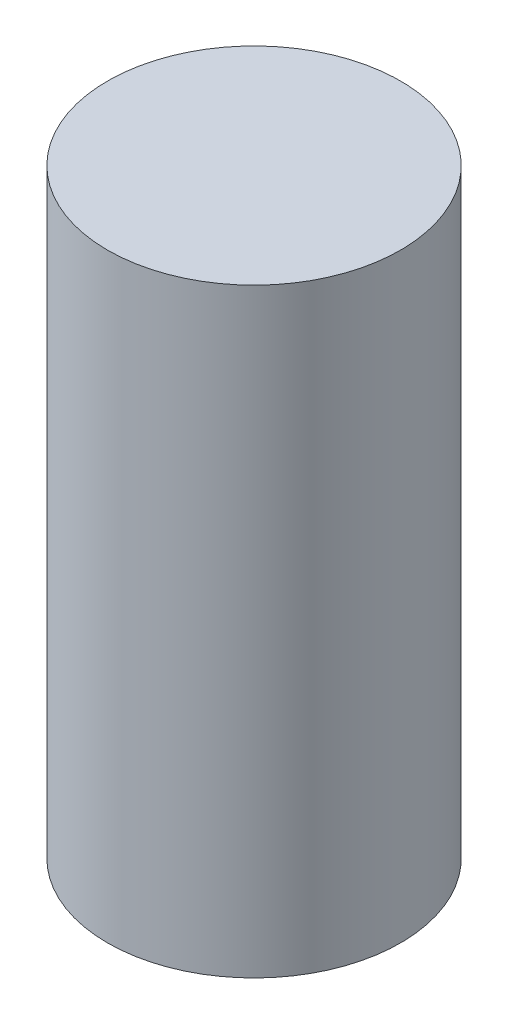
SolidWorks part; units mm, degrees
ref_plane "Front Plane" through (0, 0, 0) normal (0, 0, 1) x (1, 0, 0)
ref_plane "Top Plane" through (0, 0, 0) normal (0, 1, 0) x (1, 0, 0)
ref_plane "Right Plane" through (0, 0, 0) normal (1, 0, 0) x (0, 0, -1)
sketch "Sketch1" plane through (0, 0, 0) normal (0, 1, 0) x (1, 0, 0)
  circle A0 centre (0, 0) radius 31.5
extrude "Boss-Extrude1" add sketch "Sketch1" along normal blind 129
